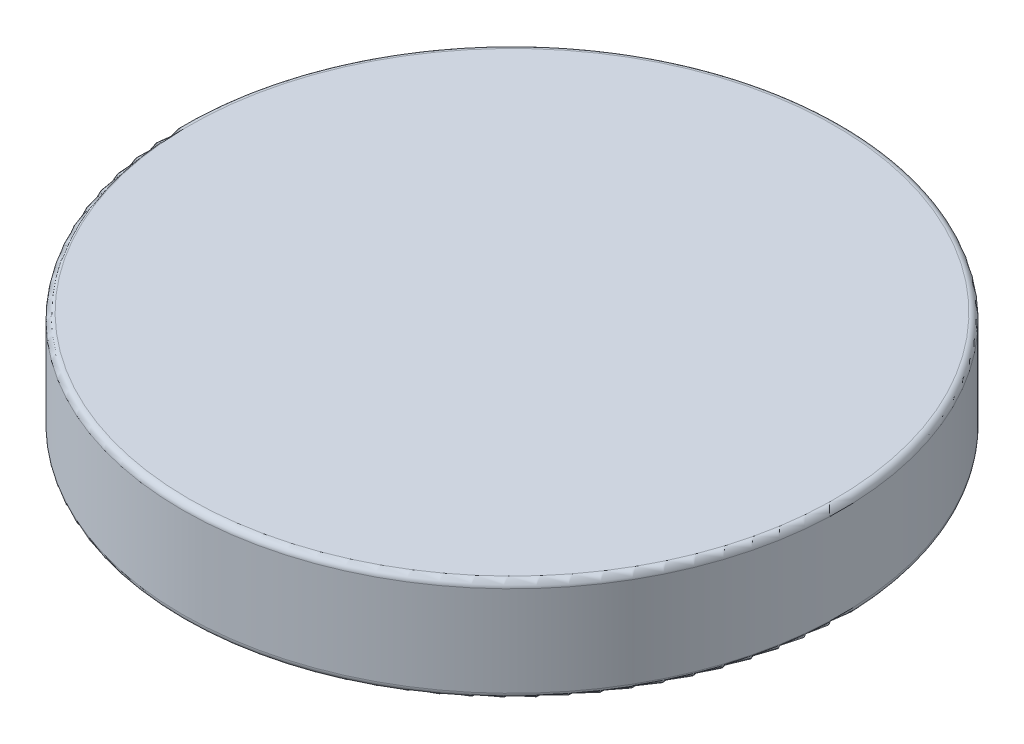
SolidWorks part; units mm, degrees
ref_plane "Front" through (0, 0, 0) normal (0, 0, 1) x (1, 0, 0)
ref_plane "Top" through (0, 0, 0) normal (0, 1, 0) x (1, 0, 0)
ref_plane "Right" through (0, 0, 0) normal (1, 0, 0) x (0, 0, -1)
sketch "Sketch2" plane through (0, 0, 0) normal (0, 1, 0) x (1, 0, 0)
  circle A0 centre (0, 0) radius 64.77
  dimension "D1" = 129.54
extrude "Boss-Extrude1" add sketch "Sketch2" against normal blind 20.32
fillet "Fillet1" radius 1.27 2 edges at (0, -20.32, 64.77) (0, 0, 64.77)
